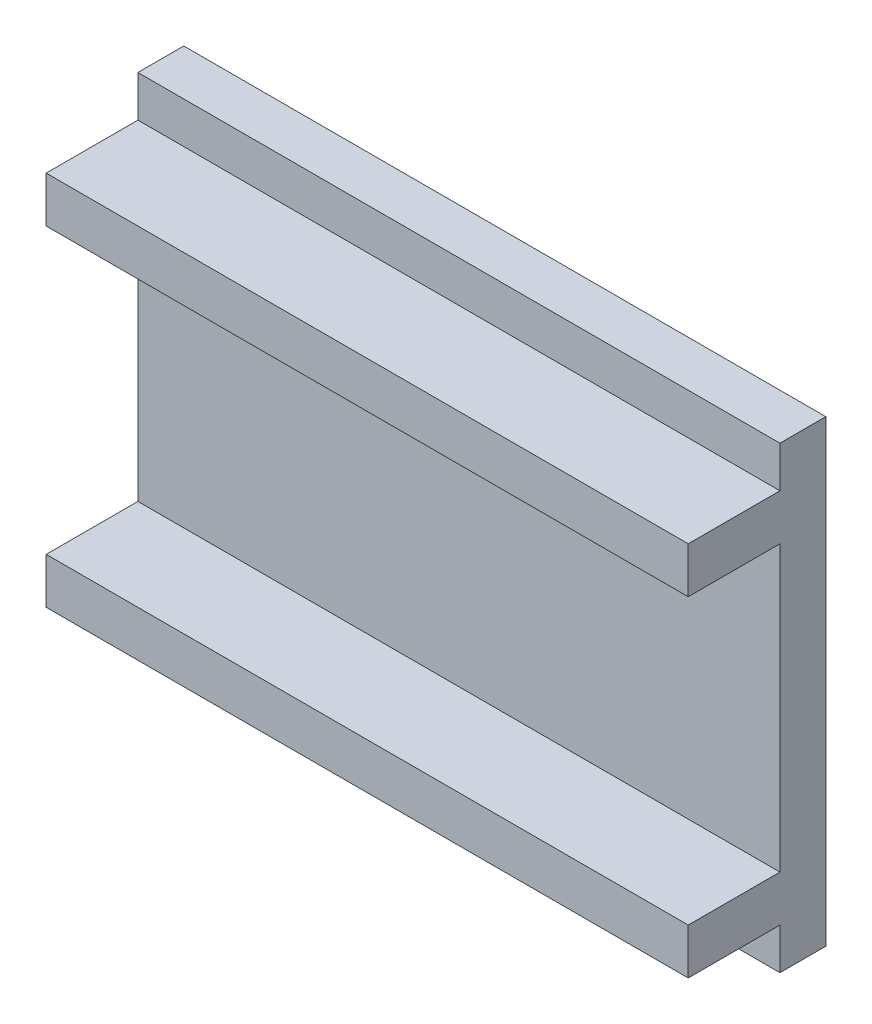
SolidWorks part; units mm, degrees
ref_plane "Front Plane" through (0, 0, 0) normal (0, 0, 1) x (1, 0, 0)
ref_plane "Top Plane" through (0, 0, 0) normal (0, 1, 0) x (1, 0, 0)
ref_plane "Right Plane" through (0, 0, 0) normal (1, 0, 0) x (0, 0, -1)
sketch "Sketch1" plane through (0, 0, 0) normal (0, 0, 1) x (1, 0, 0)
  line L1 (-35, -25) -> (35, -25)
  line L2 (-35, -25) -> (-35, 25)
  line L3 (-35, 25) -> (35, 25)
  line L4 (35, -25) -> (35, 25)
  line L5 (-35, -25) -> (35, 25) construction
  line L6 (-35, 25) -> (35, -25) construction
  point P0 (0, 0)
  dimension "D1" = 70
  dimension "D2" = 50
extrude "Boss-Extrude1" add sketch "Sketch1" along normal blind 5
sketch "Sketch2" plane through (0, 0, 5) normal (0, 0, 1) x (1, 0, 0)
  line L0 (-35, 25) -> (-35, -25) construction
  line L1 (-35, 20.5) -> (35, 20.5)
  line L2 (-35, 20.5) -> (-35, 15.5)
  line L3 (-35, 15.5) -> (35, 15.5)
  line L4 (35, 20.5) -> (35, 15.5)
  line L5 (35, -25) -> (35, 25) construction
  dimension "D1" = 5
  dimension "D2" = 15.5
extrude "Boss-Extrude2" add sketch "Sketch2" along normal blind 10
mirror "Mirror1" about plane through (0, 0, 0) normal (0, 1, 0) of "Boss-Extrude2"
